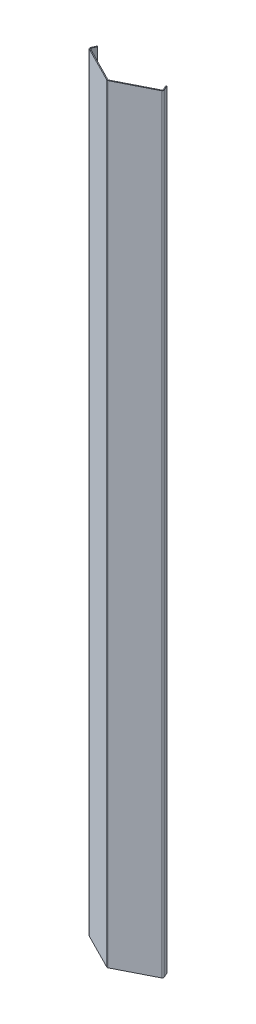
SolidWorks part; units mm, degrees
material "ASTM A36 Steel"
ref_plane "Front Plane" through (0, 0, 0) normal (0, 0, 1) x (1, 0, 0)
ref_plane "Top Plane" through (0, 0, 0) normal (0, 1, 0) x (1, 0, 0)
ref_plane "Right Plane" through (0, 0, 0) normal (1, 0, 0) x (0, 0, -1)
sketch "Sketch1" plane through (0, 0, 0) normal (0, 1, 0) x (1, 0, 0)
  line L3 (319.2222, 134.9653) -> (331.4949, 107.6505)
  line L5 (112.7099, -13.8833) -> (326.8928, 94.6317)
  line L8 (110.4502, -9.4231) -> (324.633, 99.0919)
  line L9 (314.6614, 132.9161) -> (326.9341, 105.6013)
  line L11 (314.6614, 132.9161) -> (319.2222, 134.9653)
  line L12 (-98.2806, 132.9161) -> (-102.8414, 134.9653)
  line L14 (-98.2806, 132.9161) -> (-110.5532, 105.6013)
  line L15 (105.9539, -9.4348) -> (-112.0825, 99.6134) construction
  line L16 (103.7173, -13.9067) -> (-114.3191, 95.1415) construction
  line L17 (-98.9685, 132.4295) -> (-114.1553, 106.621) construction
  line L18 (-103.2778, 134.9653) -> (-118.4645, 109.1568) construction
  line L19 (105.9307, -9.4231) -> (-108.2522, 99.0919)
  line L20 (103.6709, -13.8833) -> (-110.5119, 94.6317)
  line L21 (-102.8414, 134.9653) -> (-115.114, 107.6505)
  arc A0 (331.4949, 107.6505) -> (326.8928, 94.6317) centre (322.3733, 103.5521) cw
  arc A2 (103.6709, -13.8833) -> (112.7099, -13.8833) centre (108.1904, -4.9629) ccw
  arc A4 (105.9307, -9.4231) -> (110.4502, -9.4231) centre (108.1904, -4.9629) ccw
  arc A5 (326.9341, 105.6013) -> (324.633, 99.0919) centre (322.3733, 103.5521) cw
  arc A6 (-118.4645, 109.1568) -> (-114.3191, 95.1415) centre (-109.846, 104.0853) ccw construction
  arc A7 (-114.1553, 106.621) -> (-112.0825, 99.6134) centre (-109.846, 104.0853) ccw construction
  arc A8 (105.9539, -9.4348) -> (110.4502, -9.4231) centre (108.1904, -4.9629) ccw construction
  arc A9 (103.7173, -13.9067) -> (112.7099, -13.8833) centre (108.1904, -4.9629) ccw construction
  arc A10 (-110.5532, 105.6013) -> (-108.2522, 99.0919) centre (-105.9924, 103.5521) ccw
  arc A11 (-115.114, 107.6505) -> (-110.5119, 94.6317) centre (-105.9924, 103.5521) ccw
  point P7 (335.4063, 98.945)
  point P31 (-119.0254, 98.945)
  dimension "D2" = 10
extrude "Boss-Extrude2" add sketch "Sketch1" along normal blind 4665
